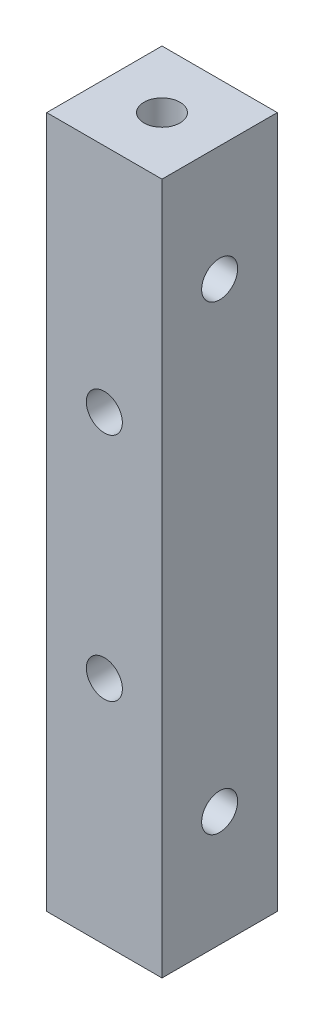
SolidWorks part; units mm, degrees
material "氧化铝"
ref_plane "前视基准面" through (0, 0, 0) normal (0, 0, 1) x (1, 0, 0)
ref_plane "上视基准面" through (0, 0, 0) normal (0, 1, 0) x (1, 0, 0)
ref_plane "右视基准面" through (0, 0, 0) normal (1, 0, 0) x (0, 0, -1)
sketch "草图1" plane through (0, 0, 0) normal (0, 1, 0) x (1, 0, 0)
  line L1 (-4, -4) -> (4, -4)
  line L2 (-4, -4) -> (-4, 4)
  line L3 (-4, 4) -> (4, 4)
  line L4 (4, -4) -> (4, 4)
  line L5 (-4, -4) -> (4, 4) construction
  line L6 (-4, 4) -> (4, -4) construction
  point P0 (0, 0)
  dimension "D1" = 8
extrude "凸台-拉伸1" add sketch "草图1" along normal mid plane 48
sketch "草图2" plane through (0, 0, 4) normal (0, 0, 1) x (1, 0, 0)
  line L0 (0, 8) -> (0, -8) construction
  line L1 (0, 0) -> (4, 0) construction
  line L2 (4, 24) -> (4, -24) construction
  dimension "D1" = 16
sketch "草图3" plane through (4, 0, 0) normal (1, 0, 0) x (0, 0, -1)
  line L0 (0, 16) -> (0, -16) construction
  line L1 (0, 0) -> (4, 0) construction
  line L2 (4, 24) -> (4, -24) construction
  dimension "D1" = 32
sketch "草图5" plane through (0, 0, 4) normal (0, 0, 1) x (1, 0, 0)
  point P0 (0, 8)
  point P3 (0, -8)
hole_wizard "M3 螺纹孔1" positions "草图5" profile "草图6" tap size "M3" standard "GB" end condition through all
sketch "草图6" plane through (0, 8, 4) normal (1, 0, 0) x (0, -1, 0)
  line L0 (0, 0) -> (0, 8)
  line L1 (0, 8) -> (1.25, 8)
  line L2 (1.25, 8) -> (1.25, 0)
  line L5 (1.25, 0) -> (0, 0)
  line L11 (0, -6.35) -> (0, 107.95) construction
  dimension "通孔螺纹孔钻头直径" = 2.5
  dimension "通孔螺纹孔钻头深度" = 8
cosmetic thread "孔螺蚊线1" parameters "D2"=3
cosmetic thread "孔螺蚊线2" parameters "D2"=3
sketch "草图7" plane through (4, 0, 0) normal (1, 0, 0) x (0, 0, -1)
  point P0 (0, 16)
  point P3 (0, -16)
hole_wizard "M3 螺纹孔2" positions "草图7" profile "草图8" tap size "M3" standard "GB" end condition through all
cosmetic thread "孔螺蚊线3" parameters "D2"=3
cosmetic thread "孔螺蚊线4" parameters "D2"=3
sketch "草图8" plane through (4, 16, 0) normal (0, 1, 0) x (0, 0, -1)
  line L0 (0, 0) -> (0, 8)
  line L1 (0, 8) -> (1.25, 8)
  line L2 (1.25, 8) -> (1.25, 0)
  line L5 (1.25, 0) -> (0, 0)
  line L11 (0, -6.35) -> (0, 107.95) construction
  dimension "通孔螺纹孔钻头直径" = 2.5
  dimension "通孔螺纹孔钻头深度" = 8
sketch "草图9" plane through (0, -24, 0) normal (0, -1, 0) x (-1, 0, 0)
  point P0 (0, 0)
hole_wizard "M3 螺纹孔3" positions "草图9" profile "草图10" tap size "M3" standard "GB" end condition through all
sketch "草图10" plane through (0, -24, 0) normal (1, 0, 0) x (0, 0, -1)
  line L0 (0, 0) -> (0, 48)
  line L1 (0, 48) -> (1.25, 48)
  line L2 (1.25, 48) -> (1.25, 0)
  line L5 (1.25, 0) -> (0, 0)
  line L11 (0, -6.35) -> (0, 107.95) construction
  dimension "通孔螺纹孔钻头直径" = 2.5
  dimension "通孔螺纹孔钻头深度" = 48
cosmetic thread "孔螺蚊线5" parameters "D2"=3
